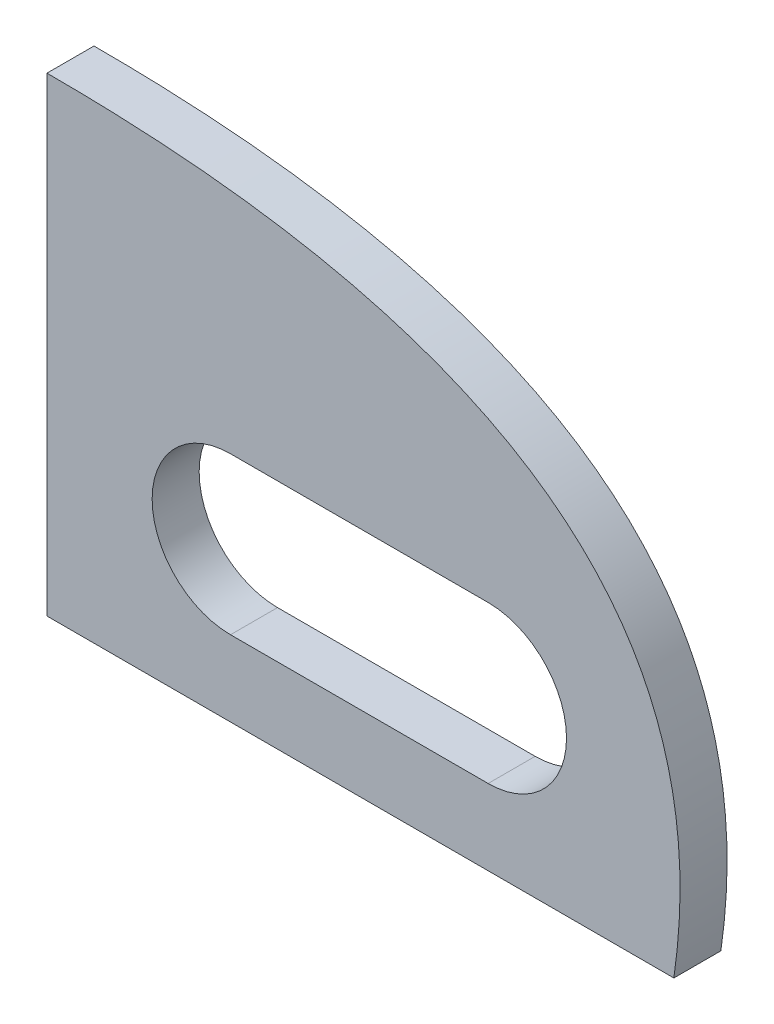
SolidWorks part; units mm, degrees
ref_plane "Front Plane" through (0, 0, 0) normal (0, 0, 1) x (1, 0, 0)
ref_plane "Top Plane" through (0, 0, 0) normal (0, 1, 0) x (1, 0, 0)
ref_plane "Right Plane" through (0, 0, 0) normal (1, 0, 0) x (0, 0, -1)
sketch "Sketch1" plane through (0, 0, 0) normal (0, 0, 1) x (1, 0, 0)
  line L0 (0, 0) -> (0, 35) construction
  line L1 (0, 0) -> (45, 0) construction
  line L2 (45, 0) -> (45, 9.8236) construction
  line L3 (45, 9.8236) -> (0, 9.8236) construction
  line L4 (0, 35) -> (0, 30) construction
  line L5 (45, 9.8236) -> (40, 9.8236) construction
  line L6 (40, 9.8236) -> (40, 0) construction
  line L9 (0, 30) -> (0, 0)
  line L10 (0, 0) -> (40, 0)
  line L11 (20, 0) -> (20, 27.9228) construction
  line L12 (11.7108, 9.8236) -> (28.1496, 9.8236) construction
  line L13 (11.7108, 14.8236) -> (28.1496, 14.8236)
  line L14 (11.7108, 4.8236) -> (28.1496, 4.8236)
  arc A0 (11.7108, 14.8236) -> (11.7108, 4.8236) centre (11.7108, 9.8236) ccw
  arc A1 (28.1496, 4.8236) -> (28.1496, 14.8236) centre (28.1496, 9.8236) ccw
  spline S1 degree 2 poles (0, 30) (44.3855, 30.0118) (40, 0) knots 0 0 0 1 1 1
  point P14 (19.9302, 9.8236)
extrude "Boss-Extrude2" add sketch "Sketch1" along normal blind 3
